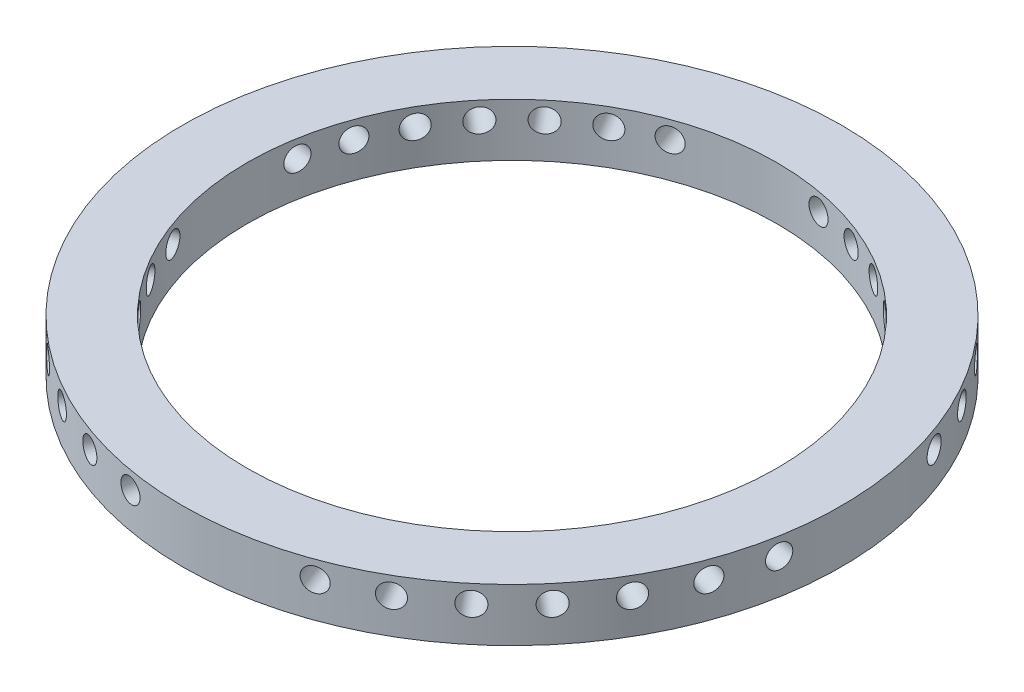
SolidWorks part; units mm, degrees
material "ABS"
ref_plane "Alzado" through (0, 0, 0) normal (0, 0, 1) x (1, 0, 0)
ref_plane "Planta" through (0, 0, 0) normal (0, 1, 0) x (1, 0, 0)
ref_plane "Vista lateral" through (0, 0, 0) normal (1, 0, 0) x (0, 0, -1)
sketch "Croquis1" plane through (0, 0, 0) normal (0, 0, 1) x (1, 0, 0)
  line L0 (0, 0) -> (-22.5, 0) construction
  line L1 (-22.5, 0) -> (-28, 0)
  line L2 (-28, 0) -> (-28, 1)
  line L3 (-28, 1) -> (-28, 4.5)
  line L4 (-22.5, 0) -> (-22.5, 4.5)
  line L5 (-22.5, 4.5) -> (-28, 4.5)
  line L6 (0, 0) -> (0, 7.1054) construction
  dimension "D1" = 22.5
  dimension "D2" = 28
  dimension "D3" = 1
  dimension "D4" = 3.5
revolve "Revolución1" add sketch "Croquis1" angle 360 about L6
ref_plane "Plano1" through (-28, 0, 0) normal (-1, 0, 0) x (0, 0, 1)
sketch "Croquis2" plane through (-28, 0, 0) normal (-1, 0, 0) x (0, 0, 1)
  line L1 (0, 4) -> (0, 4.5) construction
  line L3 (22.5, 4.5) -> (-22.5, 4.5) construction
  circle A0 centre (0, 3) radius 1
  dimension "D1" = 2
  dimension "D2" = 0.5
extrude "Cortar-Extruir1" cut sketch "Croquis2" along direction (-1, 0, 0) on the side against the normal blind 10
pattern_circular "MatrizC1" count 36 over 360 about axis through (0, 0, 0) along (0, -1, 0) of "Cortar-Extruir1"
sketch "Croquis3" plane through (0, 0, 0) normal (0, -1, 0) x (1, 0, 0)
  line L0 (-22.5, 0) -> (-22.0814, 4.3197) construction
  line L1 (-27.8695, 2.7004) -> (-26.8741, 2.6039) construction
  line L2 (-22.2907, 2.1598) -> (-27.8695, 2.7004) construction
  circle A0 centre (0, 0) radius 22.5 construction
  circle A1 centre (0, 0) radius 28 construction
  circle A2 centre (-25.0825, 2.4303) radius 1.8
  circle A3 centre (2.4303, 25.0825) radius 1.8 construction
  circle A4 centre (25.0825, -2.4303) radius 1.8 construction
  circle A5 centre (-2.4303, -25.0825) radius 1.8 construction
  point P22 (0, 0)
  dimension "D1" = 1
  dimension "D2" = 3.6
  dimension "D3" = 4
extrude "Cortar-Extruir2" cut sketch "Croquis3" against normal blind 3.5
sketch "Croquis4" plane through (0, 0, 0) normal (0, -1, 0) x (1, 0, 0)
  line L0 (-1.5181, 27.9588) -> (-1.2199, 22.4669)
  line L1 (-1.3663, 25.1629) -> (0.6337, 25.192) construction
  line L2 (2.4303, 25.0825) -> (2.17, 22.3951) construction
  line L3 (6.8576, 27.1473) -> (5.5106, 21.8148)
  line L6 (27.9588, 1.5181) -> (22.4669, 1.2199)
  line L7 (27.1473, -6.8576) -> (21.8148, -5.5106)
  line L10 (25.1629, 1.3663) -> (25.192, -0.6337) construction
  line L11 (25.0825, -2.4303) -> (22.3951, -2.17) construction
  line L14 (1.5181, -27.9588) -> (1.2199, -22.4669)
  line L15 (-6.8576, -27.1473) -> (-5.5106, -21.8148)
  line L16 (1.3663, -25.1629) -> (-0.6337, -25.192) construction
  line L17 (-2.4303, -25.0825) -> (-2.17, -22.3951) construction
  line L18 (-27.9588, -1.5181) -> (-22.4669, -1.2199)
  line L19 (-27.1473, 6.8576) -> (-21.8148, 5.5106)
  line L20 (-25.1629, -1.3663) -> (-25.192, 0.6337) construction
  line L21 (-25.0825, 2.4303) -> (-22.3951, 2.17) construction
  circle A0 centre (2.4303, 25.0825) radius 1.8 construction
  circle A1 centre (2.4303, 25.0825) radius 1.8 construction
  circle A2 centre (0, 0) radius 25.2 construction
  circle A3 centre (25.0825, -2.4303) radius 1.8 construction
  circle A4 centre (0, 0) radius 28 construction
  circle A5 centre (0, 0) radius 22.5 construction
  arc A6 (-1.5181, 27.9588) -> (6.8576, 27.1473) centre (0, 0) cw
  arc A7 (-1.2199, 22.4669) -> (5.5106, 21.8148) centre (0, 0) cw
  arc A17 (27.9588, 1.5181) -> (27.1473, -6.8576) centre (0, 0) cw
  arc A18 (22.4669, 1.2199) -> (21.8148, -5.5106) centre (0, 0) cw
  circle A19 centre (-2.4303, -25.0825) radius 1.8 construction
  arc A20 (1.5181, -27.9588) -> (-6.8576, -27.1473) centre (0, 0) cw
  arc A21 (1.2199, -22.4669) -> (-5.5106, -21.8148) centre (0, 0) cw
  circle A22 centre (-25.0825, 2.4303) radius 1.8
  arc A23 (-27.9588, -1.5181) -> (-27.1473, 6.8576) centre (0, 0) cw
  arc A24 (-22.4669, -1.2199) -> (-21.8148, 5.5106) centre (0, 0) cw
  point P57 (0, 0)
  dimension "D1" = 2
  dimension "D2" = 4
extrude "Saliente-Extruir1" add sketch "Croquis4" against normal up to surface (4.5 mm away) up to face at (0, 4.5, -28)
